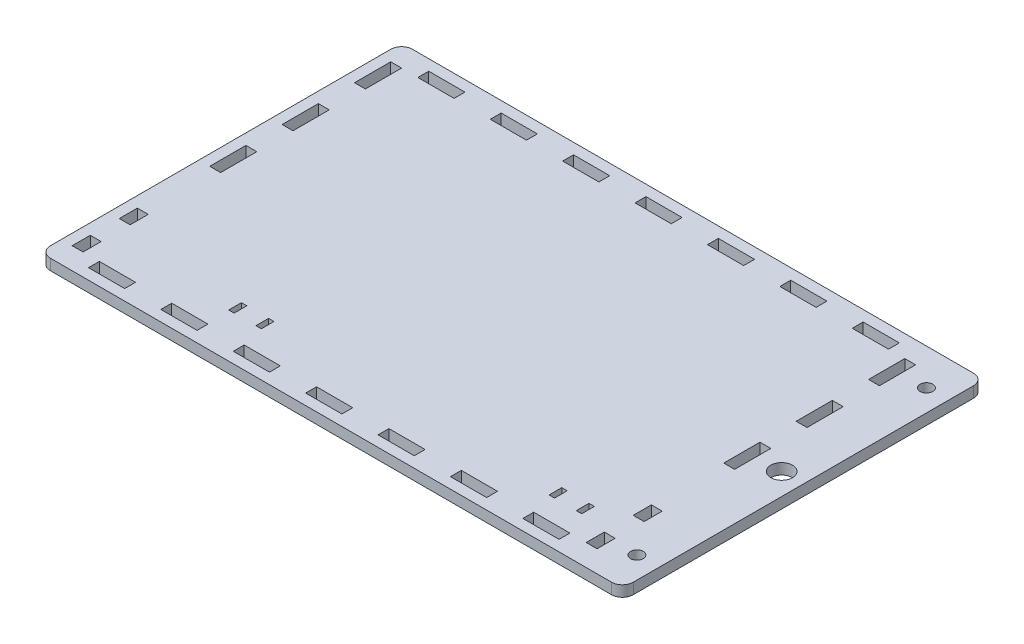
SolidWorks part; units mm, degrees
material "Maple"
ref_plane "Front Plane" through (0, 0, 0) normal (0, 0, 1) x (1, 0, 0)
ref_plane "Top Plane" through (0, 0, 0) normal (0, 1, 0) x (1, 0, 0)
ref_plane "Right Plane" through (0, 0, 0) normal (1, 0, 0) x (0, 0, -1)
sketch "Sketch1" plane through (0, 0, 0) normal (0, 1, 0) x (1, 0, 0)
  line L1 (0, 0) -> (151, 0)
  line L2 (0, 0) -> (0, -100)
  line L3 (0, -100) -> (151, -100)
  line L4 (151, 0) -> (151, -100)
  dimension "D1" = 151
  dimension "D2" = 100
extrude "Boss-Extrude1" add sketch "Sketch1" along normal blind 3
sketch "Sketch3" plane through (0, 0, 0) normal (0, -1, 0) x (1, 0, 0)
  line L0 (0, 86) -> (151, 86) construction
  line L1 (0, 100) -> (151, 100) construction
  line L2 (40, 87.75) -> (41.5, 87.75)
  line L3 (40, 87.75) -> (40, 84.25)
  line L4 (40, 84.25) -> (41.5, 84.25)
  line L5 (41.5, 87.75) -> (41.5, 84.25)
  line L6 (40, 87.75) -> (41.5, 84.25) construction
  line L7 (40, 84.25) -> (41.5, 87.75) construction
  line L8 (47.5, 87.75) -> (49, 87.75)
  line L9 (47.5, 87.75) -> (47.5, 84.25)
  line L10 (47.5, 84.25) -> (49, 84.25)
  line L11 (49, 87.75) -> (49, 84.25)
  line L12 (47.5, 87.75) -> (49, 84.25) construction
  line L13 (47.5, 84.25) -> (49, 87.75) construction
  line L14 (128.5, 87.75) -> (130, 87.75)
  line L15 (128.5, 87.75) -> (128.5, 84.25)
  line L16 (128.5, 84.25) -> (130, 84.25)
  line L17 (130, 87.75) -> (130, 84.25)
  line L18 (128.5, 87.75) -> (130, 84.25) construction
  line L19 (128.5, 84.25) -> (130, 87.75) construction
  line L20 (136, 87.75) -> (137.5, 87.75)
  line L21 (136, 87.75) -> (136, 84.25)
  line L22 (136, 84.25) -> (137.5, 84.25)
  line L23 (137.5, 87.75) -> (137.5, 84.25)
  line L24 (136, 87.75) -> (137.5, 84.25) construction
  line L25 (136, 84.25) -> (137.5, 87.75) construction
  line L26 (151, 100) -> (151, 0) construction
  line L27 (0, 0) -> (0, 100) construction
  point P2 (40.75, 86)
  point P7 (48.25, 86)
  point P12 (129.25, 86)
  point P17 (136.75, 86)
  point P24 (143.6579, 86)
  point P29 (0, 86)
  dimension "D1" = 14
  dimension "D2" = 3.5
  dimension "D3" = 1.5
  dimension "D4" = 6
  dimension "D5" = 6
  dimension "D6" = 13.5
  dimension "D7" = 40
extrude "Cut-Extrude1" cut sketch "Sketch3" against normal through all
sketch "Sketch4" plane through (0, 0, 0) normal (0, -1, 0) x (1, 0, 0)
  line L0 (151, 100) -> (151, 0) construction
  line L1 (151, 100) -> (161, 100)
  line L2 (151, 100) -> (151, 0)
  line L3 (151, 0) -> (161, 0)
  line L4 (161, 100) -> (161, 0)
  line L5 (151, 0) -> (0, 0) construction
  dimension "D1" = 10
extrude "Boss-Extrude2" add sketch "Sketch4" against normal through all
sketch "Sketch5" plane through (0, 0, 0) normal (0, -1, 0) x (1, 0, 0)
  line L0 (161, 50) -> (0, 50) construction
  line L1 (161, 0) -> (161, 100) construction
  line L2 (0, 0) -> (0, 100) construction
  line L3 (155, 100) -> (155, 0) construction
  line L4 (0, 100) -> (161, 100) construction
  line L5 (161, 0) -> (0, 0) construction
  circle A0 centre (155, 50) radius 3
  circle A1 centre (155, 90) radius 1.75
  circle A2 centre (155, 10) radius 1.75
  dimension "D1" = 6
  dimension "D3" = 3.5
  dimension "D2" = 6
  dimension "D4" = 10
  dimension "D5" = 10
  dimension "D6" = 6
extrude "Cut-Extrude2" cut sketch "Sketch5" against normal through all
fillet "Fillet1" radius 3 2 edges at (0, 1.5, 0) (0, 1.5, 100)
fillet "Fillet2" radius 3 2 edges at (161, 1.5, 100) (161, 1.5, 0)
sketch "Sketch6" plane through (0, 3, 0) normal (0, 1, 0) x (1, 0, 0)
  line L1 (148, -94) -> (145, -94)
  line L2 (148, -94) -> (148, -89)
  line L3 (148, -89) -> (145, -89)
  line L4 (145, -94) -> (145, -89)
  line L5 (148, -81) -> (145, -81)
  line L6 (148, -81) -> (148, -76)
  line L7 (148, -76) -> (145, -76)
  line L8 (145, -81) -> (145, -76)
  line L9 (148, -56) -> (145, -56)
  line L10 (148, -56) -> (148, -46)
  line L11 (148, -46) -> (145, -46)
  line L12 (145, -56) -> (145, -46)
  line L13 (148, -36) -> (145, -36)
  line L14 (148, -36) -> (148, -26)
  line L15 (148, -26) -> (145, -26)
  line L16 (145, -36) -> (145, -26)
  line L17 (148, -16) -> (145, -16)
  line L18 (148, -16) -> (148, -6)
  line L19 (148, -6) -> (145, -6)
  line L20 (145, -16) -> (145, -6)
  line L21 (140.5, -6) -> (130.5, -6)
  line L22 (140.5, -6) -> (140.5, -3)
  line L23 (140.5, -3) -> (130.5, -3)
  line L24 (130.5, -6) -> (130.5, -3)
  line L25 (120.5, -6) -> (110.5, -6)
  line L26 (120.5, -6) -> (120.5, -3)
  line L27 (120.5, -3) -> (110.5, -3)
  line L28 (110.5, -6) -> (110.5, -3)
  line L29 (100.5, -6) -> (90.5, -6)
  line L30 (100.5, -6) -> (100.5, -3)
  line L31 (100.5, -3) -> (90.5, -3)
  line L32 (90.5, -6) -> (90.5, -3)
  line L33 (80.5, -6) -> (70.5, -6)
  line L34 (80.5, -6) -> (80.5, -3)
  line L35 (80.5, -3) -> (70.5, -3)
  line L36 (70.5, -6) -> (70.5, -3)
  line L37 (60.5, -6) -> (50.5, -6)
  line L38 (60.5, -6) -> (60.5, -3)
  line L39 (60.5, -3) -> (50.5, -3)
  line L40 (50.5, -6) -> (50.5, -3)
  line L41 (40.5, -6) -> (30.5, -6)
  line L42 (40.5, -6) -> (40.5, -3)
  line L43 (40.5, -3) -> (30.5, -3)
  line L44 (30.5, -6) -> (30.5, -3)
  line L45 (20.5, -6) -> (10.5, -6)
  line L46 (20.5, -6) -> (20.5, -3)
  line L47 (20.5, -3) -> (10.5, -3)
  line L48 (10.5, -6) -> (10.5, -3)
  line L49 (6, -16) -> (3, -16)
  line L50 (6, -16) -> (6, -6)
  line L51 (6, -6) -> (3, -6)
  line L52 (3, -16) -> (3, -6)
  line L53 (6, -36) -> (3, -36)
  line L54 (6, -36) -> (6, -26)
  line L55 (6, -26) -> (3, -26)
  line L56 (3, -36) -> (3, -26)
  line L57 (6, -56) -> (3, -56)
  line L58 (6, -56) -> (6, -46)
  line L59 (6, -46) -> (3, -46)
  line L60 (3, -56) -> (3, -46)
  line L61 (6, -81) -> (3, -81)
  line L62 (6, -81) -> (6, -76)
  line L63 (6, -76) -> (3, -76)
  line L64 (3, -81) -> (3, -76)
  line L65 (6, -94) -> (3, -94)
  line L66 (6, -94) -> (6, -89)
  line L67 (6, -89) -> (3, -89)
  line L68 (3, -94) -> (3, -89)
  line L69 (20.5, -97) -> (10.5, -97)
  line L70 (20.5, -97) -> (20.5, -94)
  line L71 (20.5, -94) -> (10.5, -94)
  line L72 (10.5, -97) -> (10.5, -94)
  line L73 (40.5, -97) -> (30.5, -97)
  line L74 (40.5, -97) -> (40.5, -94)
  line L75 (40.5, -94) -> (30.5, -94)
  line L76 (30.5, -97) -> (30.5, -94)
  line L77 (60.5, -97) -> (50.5, -97)
  line L78 (60.5, -97) -> (60.5, -94)
  line L79 (60.5, -94) -> (50.5, -94)
  line L80 (50.5, -97) -> (50.5, -94)
  line L81 (80.5, -97) -> (70.5, -97)
  line L82 (80.5, -97) -> (80.5, -94)
  line L83 (80.5, -94) -> (70.5, -94)
  line L84 (70.5, -97) -> (70.5, -94)
  line L85 (100.5, -97) -> (90.5, -97)
  line L86 (100.5, -97) -> (100.5, -94)
  line L87 (100.5, -94) -> (90.5, -94)
  line L88 (90.5, -97) -> (90.5, -94)
  line L89 (120.5, -97) -> (110.5, -97)
  line L90 (120.5, -97) -> (120.5, -94)
  line L91 (120.5, -94) -> (110.5, -94)
  line L92 (110.5, -97) -> (110.5, -94)
  line L93 (140.5, -97) -> (130.5, -97)
  line L94 (140.5, -97) -> (140.5, -94)
  line L95 (140.5, -94) -> (130.5, -94)
  line L96 (130.5, -97) -> (130.5, -94)
  point P96 (148, -94)
  point P97 (147.7023, -93.7185)
  point P98 (148, -94)
extrude "Cut-Extrude3" cut sketch "Sketch6" against normal through all
equation "\"D5@Sketch5\"=\"D4@Sketch5\""
